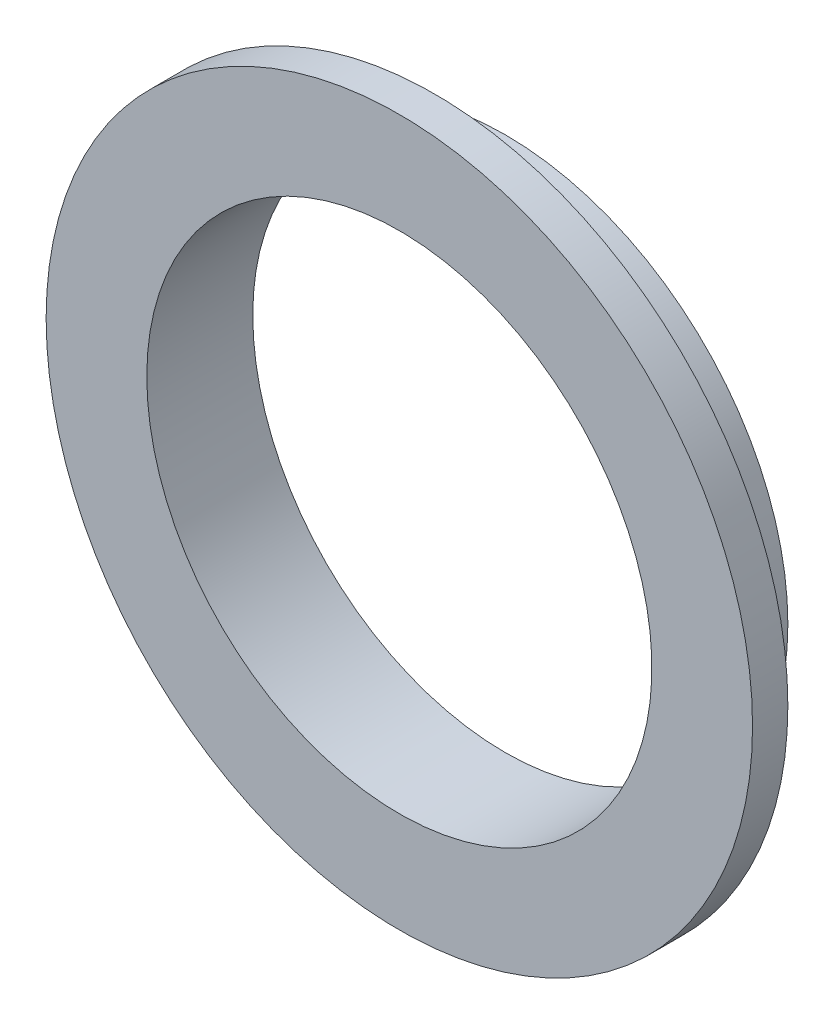
SolidWorks part; units mm, degrees
ref_plane "前视基准面" through (0, 0, 0) normal (0, 0, 1) x (1, 0, 0)
ref_plane "上视基准面" through (0, 0, 0) normal (0, 1, 0) x (1, 0, 0)
ref_plane "右视基准面" through (0, 0, 0) normal (1, 0, 0) x (0, 0, -1)
sketch "草图1" plane through (0, 0, 0) normal (0, 0, 1) x (1, 0, 0)
  circle A0 centre (0, 0) radius 16
  circle A1 centre (0, 0) radius 14.3
  dimension "D1" = 32
  dimension "D2" = 28.6
extrude "凸台-拉伸1" add sketch "草图1" along normal blind 4
sketch "草图2" plane through (0, 0, 4) normal (0, 0, 1) x (1, 0, 0)
  circle A0 centre (0, 0) radius 20
  dimension "D1" = 40
extrude "凸台-拉伸2" add sketch "草图2" along normal blind 2
sketch "草图3" plane through (0, 0, 4) normal (0, 0, -1) x (-1, 0, 0)
  circle A0 centre (0, 0) radius 14.3
extrude "切除-拉伸1" cut sketch "草图3" against normal blind 2
